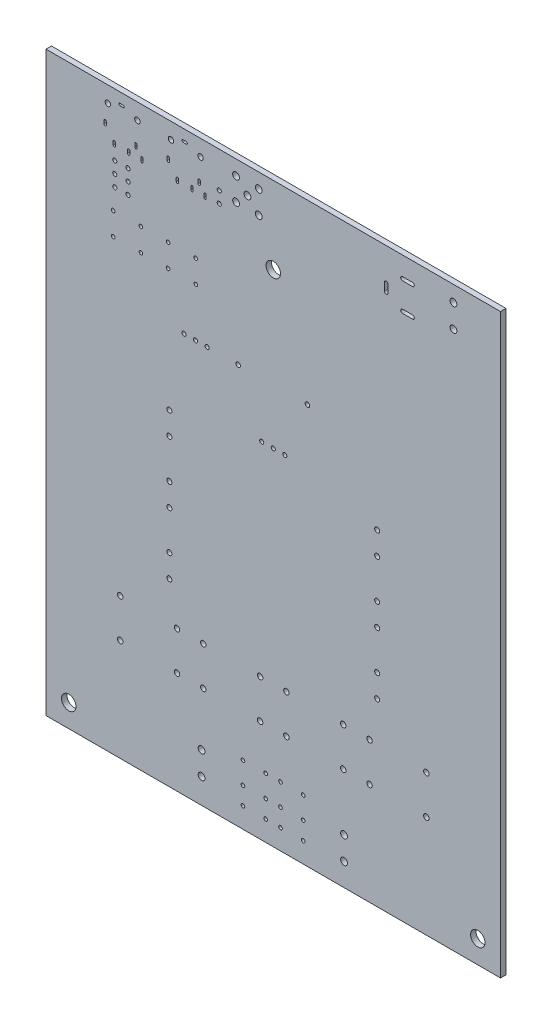
SolidWorks part; units mm, degrees
ref_plane "前视基准面" through (0, 0, 0) normal (0, 0, 1) x (1, 0, 0)
ref_plane "上视基准面" through (0, 0, 0) normal (0, 1, 0) x (1, 0, 0)
ref_plane "右视基准面" through (0, 0, 0) normal (1, 0, 0) x (0, 0, -1)
ref_plane "基准面1" through (0, 0, 0) normal (0, 0, -1) x (-1, 0, 0)
sketch "草图1" plane through (0, 0, 0) normal (0, 0, -1) x (-1, 0, 0)
  line L0 (50, 0) -> (50, 127)
  line L1 (50, 127) -> (-50, 127)
  line L2 (-50, 127) -> (-50, 0)
  line L3 (-50, 0) -> (50, 0)
  line L4 (35.2453, 116.8252) -> (35.2453, 116.1252)
  line L5 (34.7453, 116.1252) -> (34.7453, 116.8252)
  line L6 (37.2453, 119.8252) -> (37.2453, 119.1252)
  line L7 (36.7453, 119.1252) -> (36.7453, 119.8252)
  line L8 (33.7453, 124.3252) -> (33.0453, 124.3252)
  line L9 (33.0453, 124.8252) -> (33.7453, 124.8252)
  line L10 (32.0453, 116.8252) -> (32.0453, 116.1252)
  line L11 (31.5453, 116.1252) -> (31.5453, 116.8252)
  line L12 (18.1568, 116.8252) -> (18.1568, 116.1252)
  line L13 (17.6568, 116.1252) -> (17.6568, 116.8252)
  line L14 (29.1453, 116.8252) -> (29.1453, 116.1252)
  line L15 (28.6453, 116.1252) -> (28.6453, 116.8252)
  line L16 (21.3568, 116.8252) -> (21.3568, 116.1252)
  line L17 (20.8568, 116.1252) -> (20.8568, 116.8252)
  line L18 (16.5568, 118.8252) -> (16.5568, 118.1252)
  line L19 (16.0568, 118.1252) -> (16.0568, 118.8252)
  line L20 (15.2568, 116.8252) -> (15.2568, 116.1252)
  line L21 (14.7568, 116.1252) -> (14.7568, 116.8252)
  line L22 (30.4453, 118.8252) -> (30.4453, 118.1252)
  line L23 (29.9453, 118.1252) -> (29.9453, 118.8252)
  line L24 (23.3568, 119.8252) -> (23.3568, 119.1252)
  line L25 (22.8568, 119.1252) -> (22.8568, 119.8252)
  line L26 (19.8568, 124.3252) -> (19.1568, 124.3252)
  line L27 (19.1568, 124.8252) -> (19.8568, 124.8252)
  line L28 (-25.2402, 118.1252) -> (-25.2402, 119.8252)
  line L29 (-24.4402, 119.8252) -> (-24.4402, 118.1252)
  line L30 (-30.6402, 116.6752) -> (-28.4402, 116.6752)
  line L31 (-28.4402, 115.8752) -> (-30.6402, 115.8752)
  line L32 (-30.6402, 122.8752) -> (-28.4402, 122.8752)
  line L33 (-28.4402, 122.0752) -> (-30.6402, 122.0752)
  circle A0 centre (45, 5) radius 1.5875
  circle A1 centre (33.682, 31) radius 0.6
  circle A2 centre (33.682, 22.5) radius 0.6
  circle A3 centre (22.86, 39.6255) radius 0.55
  circle A4 centre (22.86, 53.2145) radius 0.55
  circle A5 centre (22.86, 44.6255) radius 0.55
  circle A6 centre (35.2298, 98.6428) radius 0.4
  circle A7 centre (29.1338, 103.6428) radius 0.4
  circle A8 centre (29.1338, 98.6428) radius 0.4
  circle A9 centre (22.86, 58.2145) radius 0.55
  circle A10 centre (23.147, 103.6428) radius 0.4
  circle A11 centre (23.147, 98.6428) radius 0.4
  circle A12 centre (15.7734, 5.5118) radius 0.75
  circle A13 centre (21.182, 31) radius 0.6
  circle A14 centre (21.182, 22.5) radius 0.6
  circle A15 centre (15.7734, 10.5918) radius 0.75
  circle A16 centre (15.394, 31) radius 0.6
  circle A17 centre (15.394, 22.5) radius 0.6
  circle A18 centre (22.86, 66.8035) radius 0.55
  circle A19 centre (22.86, 71.8035) radius 0.55
  circle A20 centre (19.6342, 87.964) radius 0.45
  circle A21 centre (17.0942, 87.964) radius 0.45
  circle A22 centre (17.0594, 98.6428) radius 0.4
  circle A23 centre (14.5542, 87.964) radius 0.45
  circle A24 centre (35.2298, 103.6428) radius 0.4
  circle A25 centre (34.8742, 110.7948) radius 0.45
  circle A26 centre (34.8742, 108.2548) radius 0.45
  circle A27 centre (31.9532, 108.2548) radius 0.45
  circle A28 centre (34.8742, 113.3348) radius 0.45
  circle A29 centre (31.9532, 110.7948) radius 0.45
  arc A30 (35.2453, 116.1252) -> (34.7453, 116.1252) centre (34.9953, 116.1252) cw
  arc A31 (34.7453, 116.8252) -> (35.2453, 116.8252) centre (34.9953, 116.8252) cw
  arc A32 (37.2453, 119.1252) -> (36.7453, 119.1252) centre (36.9953, 119.1252) cw
  arc A33 (36.7453, 119.8252) -> (37.2453, 119.8252) centre (36.9953, 119.8252) cw
  circle A34 centre (36.3953, 123.4752) radius 0.6
  circle A35 centre (31.9532, 113.3348) radius 0.45
  arc A36 (33.0453, 124.3252) -> (33.0453, 124.8252) centre (33.0453, 124.5752) cw
  arc A37 (33.7453, 124.8252) -> (33.7453, 124.3252) centre (33.7453, 124.5752) cw
  arc A38 (32.0453, 116.1252) -> (31.5453, 116.1252) centre (31.7953, 116.1252) cw
  arc A39 (31.5453, 116.8252) -> (32.0453, 116.8252) centre (31.7953, 116.8252) cw
  arc A40 (18.1568, 116.1252) -> (17.6568, 116.1252) centre (17.9068, 116.1252) cw
  arc A41 (17.6568, 116.8252) -> (18.1568, 116.8252) centre (17.9068, 116.8252) cw
  arc A42 (29.1453, 116.1252) -> (28.6453, 116.1252) centre (28.8953, 116.1252) cw
  arc A43 (28.6453, 116.8252) -> (29.1453, 116.8252) centre (28.8953, 116.8252) cw
  arc A44 (21.3568, 116.1252) -> (20.8568, 116.1252) centre (21.1068, 116.1252) cw
  arc A45 (20.8568, 116.8252) -> (21.3568, 116.8252) centre (21.1068, 116.8252) cw
  circle A46 centre (17.0594, 103.6428) radius 0.4
  arc A47 (16.5568, 118.1252) -> (16.0568, 118.1252) centre (16.3068, 118.1252) cw
  arc A48 (16.0568, 118.8252) -> (16.5568, 118.8252) centre (16.3068, 118.8252) cw
  arc A49 (15.2568, 116.1252) -> (14.7568, 116.1252) centre (15.0068, 116.1252) cw
  arc A50 (14.7568, 116.8252) -> (15.2568, 116.8252) centre (15.0068, 116.8252) cw
  arc A51 (30.4453, 118.1252) -> (29.9453, 118.1252) centre (30.1953, 118.1252) cw
  arc A52 (29.9453, 118.8252) -> (30.4453, 118.8252) centre (30.1953, 118.8252) cw
  circle A53 centre (29.8953, 123.4752) radius 0.6
  arc A54 (23.3568, 119.1252) -> (22.8568, 119.1252) centre (23.1068, 119.1252) cw
  arc A55 (22.8568, 119.8252) -> (23.3568, 119.8252) centre (23.1068, 119.8252) cw
  circle A56 centre (22.5068, 123.4752) radius 0.6
  arc A57 (19.1568, 124.3252) -> (19.1568, 124.8252) centre (19.1568, 124.5752) cw
  arc A58 (19.8568, 124.8252) -> (19.8568, 124.3252) centre (19.8568, 124.5752) cw
  circle A59 centre (16.0068, 123.4752) radius 0.6
  circle A60 centre (6.671, 4.4638) radius 0.4
  circle A61 centre (6.671, 8.3681) radius 0.4
  circle A62 centre (1.671, 4.4638) radius 0.4
  circle A63 centre (-1.591, 4.4638) radius 0.4
  circle A64 centre (1.671, 8.3681) radius 0.4
  circle A65 centre (-1.591, 8.3681) radius 0.4
  circle A66 centre (6.671, 13.168) radius 0.4
  circle A67 centre (2.894, 31) radius 0.6
  circle A68 centre (2.894, 22.5) radius 0.6
  circle A69 centre (1.671, 13.168) radius 0.4
  circle A70 centre (-1.591, 13.168) radius 0.4
  circle A71 centre (-2.894, 31) radius 0.6
  circle A72 centre (-6.591, 4.4638) radius 0.4
  circle A73 centre (-6.591, 13.168) radius 0.4
  circle A74 centre (-6.591, 8.3681) radius 0.4
  circle A75 centre (-45, 5) radius 1.5875
  circle A76 centre (-15.5702, 10.0838) radius 0.75
  circle A77 centre (-15.5702, 5.0038) radius 0.75
  circle A78 centre (-21.182, 22.5) radius 0.6
  circle A79 centre (-2.894, 22.5) radius 0.6
  circle A80 centre (-15.394, 22.5) radius 0.6
  circle A81 centre (-33.682, 22.5) radius 0.6
  circle A82 centre (-21.182, 31) radius 0.6
  circle A83 centre (-33.682, 31) radius 0.6
  circle A84 centre (2.54, 75.9244) radius 0.45
  circle A85 centre (11.8872, 116.6114) radius 0.45
  circle A86 centre (7.7216, 88.0148) radius 0.5
  circle A87 centre (-2.54, 75.9244) radius 0.45
  circle A88 centre (0, 75.9244) radius 0.45
  circle A89 centre (0, 110) radius 1.5875
  circle A90 centre (8.1896, 118.7596) radius 0.75
  circle A91 centre (11.8872, 119.1514) radius 0.45
  circle A92 centre (8.1896, 123.7596) radius 0.75
  circle A93 centre (3.1896, 118.7596) radius 0.75
  circle A94 centre (5.6896, 121.2596) radius 0.75
  circle A95 centre (3.1896, 123.7596) radius 0.75
  circle A96 centre (-15.394, 31) radius 0.6
  circle A97 centre (-22.86, 44.6255) radius 0.55
  circle A98 centre (-22.86, 39.6255) radius 0.55
  circle A99 centre (-22.86, 53.2145) radius 0.55
  circle A100 centre (-22.86, 66.8035) radius 0.55
  circle A101 centre (-22.86, 58.2145) radius 0.55
  circle A102 centre (-22.86, 71.8035) radius 0.55
  circle A103 centre (-7.5184, 88.0148) radius 0.5
  arc A104 (-25.2402, 119.8252) -> (-24.4402, 119.8252) centre (-24.8402, 119.8252) cw
  arc A105 (-24.4402, 118.1252) -> (-25.2402, 118.1252) centre (-24.8402, 118.1252) cw
  arc A106 (-28.4402, 116.6752) -> (-28.4402, 115.8752) centre (-28.4402, 116.2752) cw
  arc A107 (-30.6402, 115.8752) -> (-30.6402, 116.6752) centre (-30.6402, 116.2752) cw
  circle A108 centre (-39.6494, 118.4656) radius 0.75
  arc A109 (-28.4402, 122.8752) -> (-28.4402, 122.0752) centre (-28.4402, 122.4752) cw
  arc A110 (-30.6402, 122.0752) -> (-30.6402, 122.8752) centre (-30.6402, 122.4752) cw
  circle A111 centre (-39.6494, 123.5456) radius 0.75
extrude "凸台-拉伸1" add sketch "草图1" against normal blind 1.2
